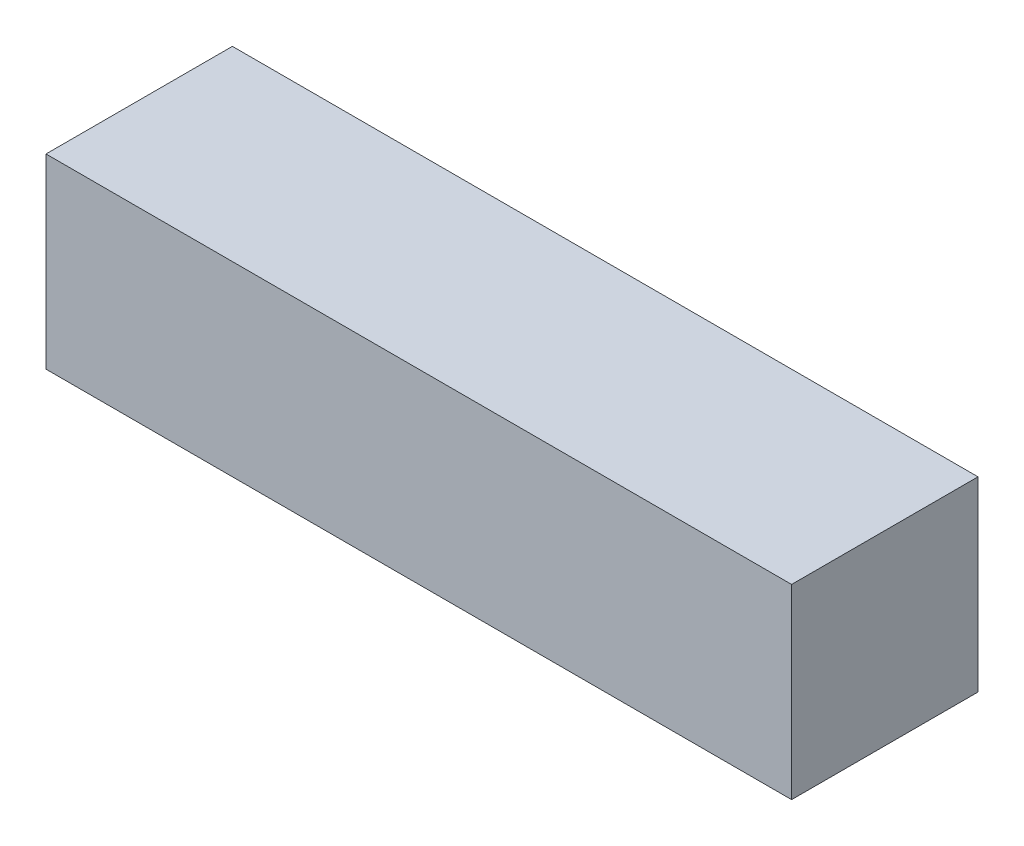
SolidWorks part; units mm, degrees
ref_plane "Ebene vorne" through (0, 0, 0) normal (0, 0, 1) x (1, 0, 0)
ref_plane "Ebene oben" through (0, 0, 0) normal (0, 1, 0) x (1, 0, 0)
ref_plane "Ebene rechts" through (0, 0, 0) normal (1, 0, 0) x (0, 0, -1)
other "Center of Mass"
sketch "Sketch1" plane through (0, 0, 0) normal (1, 0, 0) x (0, 0, -1)
  line L0 (-106.9498, 0) -> (127.027, 0) construction
  line L1 (-50, 50) -> (50, 50)
  line L2 (-50, 50) -> (-50, -50)
  line L3 (-50, -50) -> (50, -50)
  line L4 (50, 50) -> (50, -50)
  line L5 (0, 87.8378) -> (0, -79.3436) construction
  dimension "D1" = 100
extrude "Boss-Extrude1" add sketch "Sketch1" along normal blind 400
sketch "Sketch2" plane through (0, 0, 0) normal (-1, 0, 0) x (0, 0, 1)
  circle A0 centre (0, 0) radius 4
  dimension "D1" = 8
extrude "Cut-Extrude1" cut sketch "Sketch2" against normal blind 10
